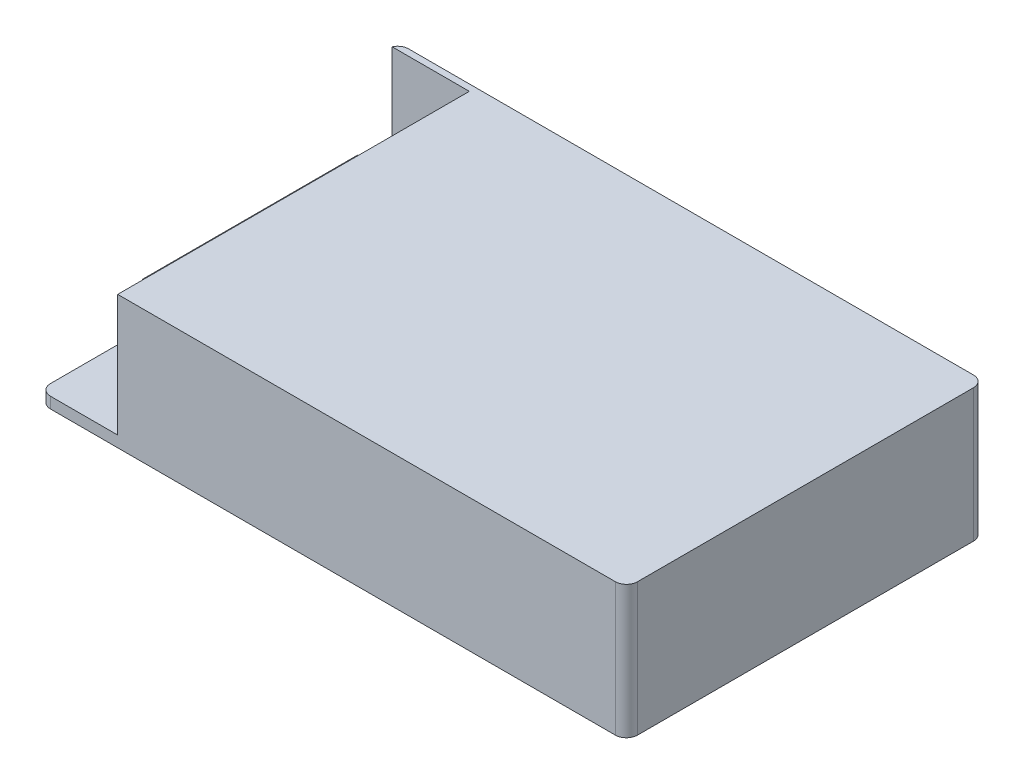
SolidWorks part; units mm, degrees
ref_plane "Front Plane" through (0, 0, 0) normal (0, 0, 1) x (1, 0, 0)
ref_plane "Top Plane" through (0, 0, 0) normal (0, 1, 0) x (1, 0, 0)
ref_plane "Right Plane" through (0, 0, 0) normal (1, 0, 0) x (0, 0, -1)
sketch "Sketch1" plane through (0, 0, 0) normal (0, 1, 0) x (1, 0, 0)
  line L1 (-76.5, 48.5) -> (76.5, 48.5)
  line L2 (-79.5, 45.5) -> (-79.5, -45.5)
  line L3 (-76.5, -48.5) -> (76.5, -48.5)
  line L4 (79.5, 45.5) -> (79.5, -45.5)
  line L5 (-79.5, 48.5) -> (79.5, -48.5) construction
  line L6 (-79.5, -48.5) -> (79.5, 48.5) construction
  arc A0 (79.5, -45.5) -> (76.5, -48.5) centre (76.5, -45.5) cw
  arc A1 (79.5, 45.5) -> (76.5, 48.5) centre (76.5, 45.5) ccw
  arc A2 (-79.5, 45.5) -> (-76.5, 48.5) centre (-76.5, 45.5) cw
  arc A3 (-79.5, -45.5) -> (-76.5, -48.5) centre (-76.5, -45.5) ccw
  point P0 (0, 0)
  dimension "D1" = 3
  dimension "D2" = 97
  dimension "D3" = 159
extrude "Boss-Extrude1" add sketch "Sketch1" along normal blind 36
sketch "Sketch2" plane through (0, 36, 0) normal (0, 1, 0) x (1, 0, 0)
  line L1 (-83.4067, 46.7561) -> (-58.3139, 46.7561)
  line L2 (-83.4067, 46.7561) -> (-83.4067, -51.2626)
  line L3 (-83.4067, -51.2626) -> (-58.3139, -51.2626)
  line L4 (-58.3139, 46.7561) -> (-58.3139, -51.2626)
extrude "Cut-Extrude1" cut sketch "Sketch2" against normal blind 33
sketch "Sketch3" plane through (0, 3, 0) normal (0, 1, 0) x (1, 0, 0)
  line L0 (-79.5, 45.5) -> (-79.5, -45.5) construction
  line L1 (-79.5, 37.7045) -> (-58.3139, 37.7045)
  line L2 (-79.5, 37.7045) -> (-79.5, -20.5839)
  line L3 (-79.5, -20.5839) -> (-58.3139, -20.5839)
  line L4 (-58.3139, 37.7045) -> (-58.3139, -20.5839)
  line L5 (-58.3139, 46.7561) -> (-58.3139, -48.5) construction
extrude "Boss-Extrude2" add sketch "Sketch3" along normal blind 12 separate body
